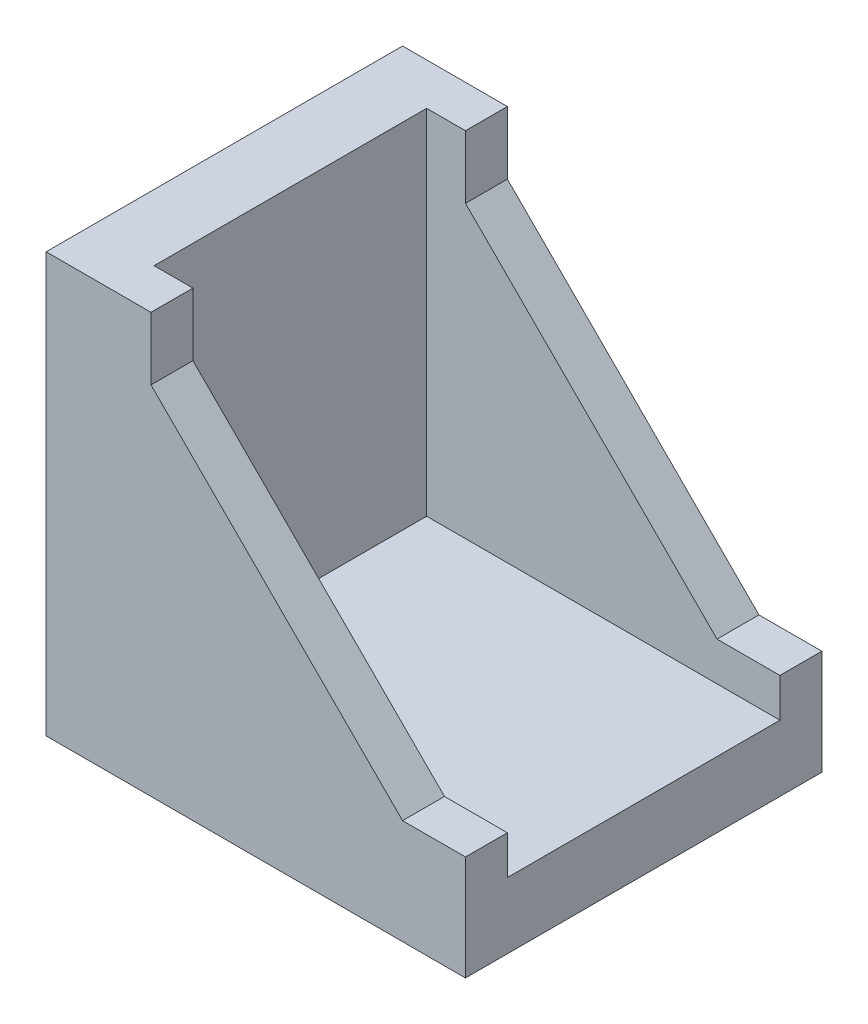
SolidWorks part; units mm, degrees
ref_plane "前视基准面" through (0, 0, 0) normal (0, 0, 1) x (1, 0, 0)
ref_plane "上视基准面" through (0, 0, 0) normal (0, 1, 0) x (1, 0, 0)
ref_plane "右视基准面" through (0, 0, 0) normal (1, 0, 0) x (0, 0, -1)
sketch "草图1" plane through (0, 0, 0) normal (0, 0, 1) x (1, 0, 0)
  line L0 (0, 0) -> (20, 0)
  line L1 (20, 0) -> (20, 5)
  line L2 (20, 5) -> (17, 5)
  line L3 (0, 0) -> (0, 20)
  line L4 (0, 20) -> (5, 20)
  line L5 (5, 20) -> (5, 17)
  line L6 (5, 17) -> (17, 5)
extrude "凸台-拉伸1" add sketch "草图1" along normal blind 17
sketch "草图2" plane through (20, 0, 0) normal (1, 0, 0) x (0, 0, -1)
  line L1 (-15, 3.15) -> (-2, 3.15)
  line L2 (-15, 3.15) -> (-15, 20.642)
  line L3 (-15, 20.642) -> (-2, 20.642)
  line L4 (-2, 3.15) -> (-2, 20.642)
extrude "切除-拉伸1" cut sketch "草图2" against normal blind 16.85
